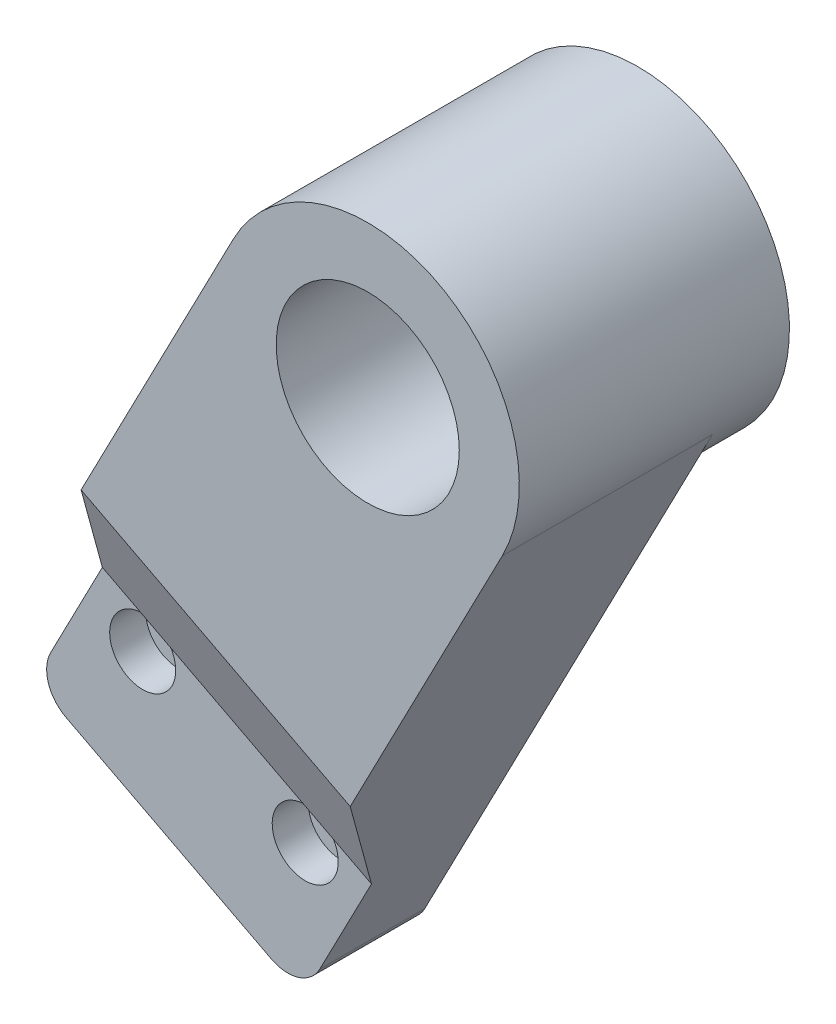
SolidWorks part; units mm, degrees
ref_plane "前视基准面" through (0, 0, 0) normal (0, 0, 1) x (1, 0, 0)
ref_plane "上视基准面" through (0, 0, 0) normal (0, 1, 0) x (1, 0, 0)
ref_plane "右视基准面" through (0, 0, 0) normal (1, 0, 0) x (0, 0, -1)
other "Configuration Table"
sketch "草图1" plane through (0, 0, 0) normal (0, 0, 1) x (1, 0, 0)
  circle A0 centre (0, 0) radius 7.625
  circle A1 centre (0, 0) radius 12.625
  dimension "D1" = 15.25
  dimension "D2" = 5
extrude "凸台-拉伸1" add sketch "草图1" against normal up to surface (22.5 mm away)
sketch "草图2" plane through (0, 0, 0) normal (0, 0, 1) x (1, 0, 0)
  line L0 (0, 0) -> (-21.873, -42.1533) construction
  line L1 (14.7586, -14.9811) -> (17.2458, -10.1879) construction
  line L2 (11.2062, -5.8148) -> (-14.1256, -54.6339)
  line L3 (-14.1256, -54.6339) -> (-36.538, -43.0043)
  line L4 (-36.538, -43.0043) -> (-11.2062, 5.8148)
  line L7 (-34.1689, -8.0031) -> (-5.0461, -23.1147) construction
  circle A0 centre (0, 0) radius 12.625 construction
  arc A1 (-11.2062, 5.8148) -> (11.2062, -5.8148) centre (0, 0) ccw
  dimension "D1" = 55
extrude "凸台-拉伸2" add sketch "草图2" against normal up to surface (17.5 mm away)
sketch "草图3" plane through (-11.2062, 5.8148, 0) normal (-0.8876, 0.4606, 0) x (0, 0, 1)
  line L0 (-8.75, -55) -> (-8.75, -42.6554)
  line L1 (-17.5, -55) -> (0, -55) construction
  line L2 (-8.75, -42.6554) -> (0, -27.5)
  line L3 (0, 0) -> (0, -55) construction
  line L4 (0, -27.5) -> (0, -55)
  line L5 (0, -55) -> (-8.75, -55)
  dimension "D1" = 150
extrude "切除-拉伸1" cut sketch "草图3" against normal through all
fillet "圆角1" radius 3 2 edges at (-14.1256, -54.6339, -13.125) (-36.538, -43.0043, -13.125)
sketch "草图4" plane through (0, 0, -8.75) normal (0, 0, 1) x (1, 0, 0)
  line L0 (-25.4572, -49.0607) -> (31.4107, 60.5343) construction
  line L3 (15.7301, 2.9037) -> (-0.8426, -29.0351) construction
  line L4 (-16.7884, -53.2521) -> (-33.8751, -44.386) construction
  line L5 (-12.7438, -51.971) -> (-8.4399, -43.6766) construction
  circle A2 centre (-13.9579, -43.4548) radius 1.6
  circle A3 centre (-27.4941, -36.431) radius 1.6
  point P9 (-25.3318, -48.8191)
  dimension "D1" = 3.2
  dimension "D2" = 5
  dimension "D3" = 10
extrude "切除-拉伸5" cut sketch "草图4" against normal through all
sketch "草图5" plane through (0, 0, -8.75) normal (0, 0, 1) x (1, 0, 0)
  circle A0 centre (-13.9579, -43.4548) radius 2.75
  circle A1 centre (-27.4941, -36.431) radius 1.6
  circle A2 centre (-27.4941, -36.431) radius 1.6 construction
  circle A3 centre (-13.9579, -43.4548) radius 1.6
  circle A4 centre (-13.9579, -43.4548) radius 1.6 construction
  circle A6 centre (-27.4941, -36.431) radius 2.75
  dimension "D3" = 5.5
  dimension "D1" = 0
  dimension "D2" = 0
extrude "切除-拉伸6" cut sketch "草图5" against normal blind 3
